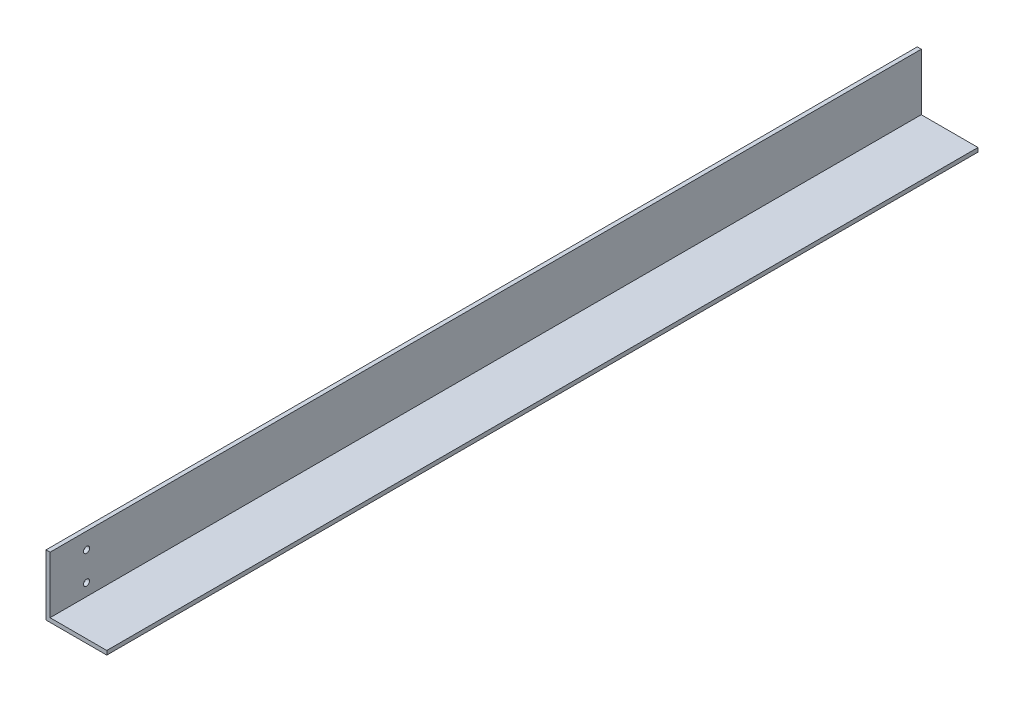
SolidWorks part; units mm, degrees
material "1060 Alloy"
ref_plane "Front Plane" through (0, 0, 0) normal (0, 0, 1) x (1, 0, 0)
ref_plane "Top Plane" through (0, 0, 0) normal (0, 1, 0) x (1, 0, 0)
ref_plane "Right Plane" through (0, 0, 0) normal (1, 0, 0) x (0, 0, -1)
sketch "Sketch1" plane through (0, 0, 0) normal (0, 0, 1) x (1, 0, 0)
  line L0 (0, 5.6023) -> (0, 35.6023)
  line L1 (0, 35.6023) -> (2, 35.6023)
  line L2 (2, 35.6023) -> (2, 7.6023)
  line L3 (2, 7.6023) -> (30, 7.6023)
  line L4 (30, 7.6023) -> (30, 5.6023)
  line L5 (30, 5.6023) -> (0, 5.6023)
extrude "Boss-Extrude1" add sketch "Sketch1" along normal blind 410 and the other way up to vertex (20 mm away)
hole_wizard "Ø3.0 (3) Diameter Hole1" positions "Sketch2" profile "Sketch3" hole size "Ø3.0" standard "ISO" end condition through all
sketch "Sketch2" plane through (0, 136.4643, 221.32) normal (-1, 0, 0) x (0, 1, 0)
  circle A0 centre (-108.862, -170.68) radius 1.5
  circle A1 centre (215.138, -170.68) radius 1.5
  circle A2 centre (201.138, -170.68) radius 1.5
  point P0 (-122.862, -170.68)
  point P1 (-108.862, -170.68)
  point P3 (215.138, -170.68)
  point P7 (201.138, -170.68)
  point P9 (201.138, -170.68)
  point P10 (215.138, -170.68)
sketch "Sketch3" plane through (0, 13.6023, 392) normal (0, 1, 0) x (0, 0, 1)
  line L0 (0, 0) -> (0, 30)
  line L1 (0, 30) -> (1.5, 30)
  line L2 (1.5, 30) -> (1.5, 0)
  line L5 (1.5, 0) -> (0, 0)
  line L11 (0, -6.35) -> (0, 107.95) construction
  dimension "Thru Hole Dia." = 3
  dimension "Thru Hole Depth" = 30
